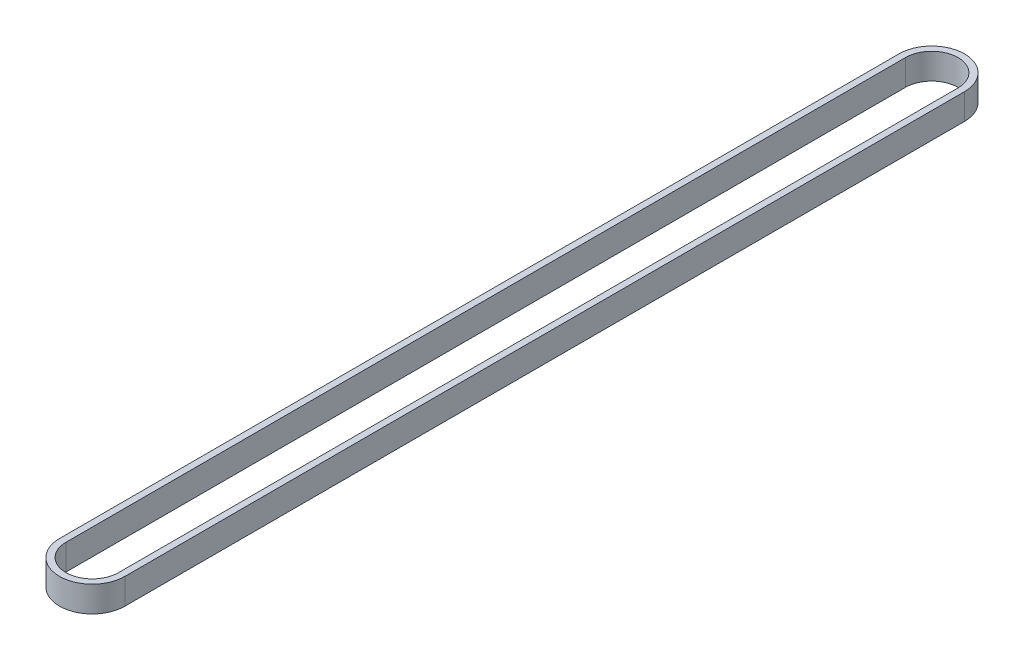
SolidWorks part; units mm, degrees
material "天然橡胶"
ref_plane "前视基准面" through (0, 0, 0) normal (0, 0, 1) x (1, 0, 0)
ref_plane "上视基准面" through (0, 0, 0) normal (0, 1, 0) x (1, 0, 0)
ref_plane "右视基准面" through (0, 0, 0) normal (1, 0, 0) x (0, 0, -1)
other "Configuration Table"
sketch "草图1" plane through (0, 0, 0) normal (0, 1, 0) x (1, 0, 0)
  line L0 (0, -97.55) -> (0, 97.55) construction
  line L1 (-7.61, -97.55) -> (-7.61, 97.55)
  line L2 (7.61, -97.55) -> (7.61, 97.55)
  line L3 (0, -97.55) -> (0, 97.55) construction
  line L4 (-6.11, -97.55) -> (-6.11, 97.55)
  line L5 (6.11, -97.55) -> (6.11, 97.55)
  arc A0 (-7.61, -97.55) -> (7.61, -97.55) centre (0, -97.55) ccw
  arc A1 (7.61, 97.55) -> (-7.61, 97.55) centre (0, 97.55) ccw
  arc A2 (-6.11, -97.55) -> (6.11, -97.55) centre (0, -97.55) ccw
  arc A3 (6.11, 97.55) -> (-6.11, 97.55) centre (0, 97.55) ccw
  point P2 (0, 0)
  point P9 (0, 0)
  dimension "D3" = 6.11
  dimension "D4" = 7.61
  dimension "D1" = 195.1
  dimension "D2" = 195.1
extrude "凸台-拉伸1" add sketch "草图1" along normal blind 6
